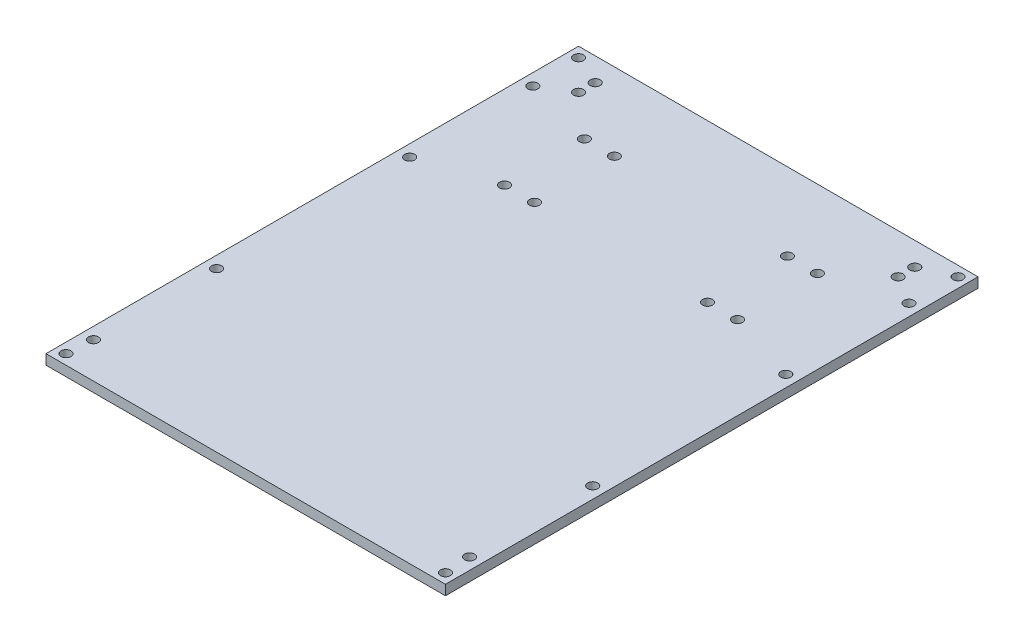
SolidWorks part; units mm, degrees
ref_plane "Front Plane" through (0, 0, 0) normal (0, 0, 1) x (1, 0, 0)
ref_plane "Top Plane" through (0, 0, 0) normal (0, 1, 0) x (1, 0, 0)
ref_plane "Right Plane" through (0, 0, 0) normal (1, 0, 0) x (0, 0, -1)
sketch "Sketch1" plane through (0, 0, 0) normal (0, 1, 0) x (1, 0, 0)
  line L1 (-120, 160) -> (0, 160)
  line L2 (-120, 160) -> (-120, 0)
  line L3 (-120, 0) -> (0, 0)
  line L4 (0, 160) -> (0, 0)
  dimension "D1" = 120
  dimension "D2" = 160
extrude "Boss-Extrude1" add sketch "Sketch1" along normal blind 3
sketch "Sketch2" plane through (0, 3, 0) normal (0, 1, 0) x (1, 0, 0)
  line L0 (-60, 160) -> (-60, 0)
  line L1 (0, 160) -> (-120, 160) construction
  line L2 (-120, 0) -> (0, 0) construction
  line L3 (0, 0) -> (0, 160) construction
  circle A0 centre (-3.5, 47.75) radius 1.5
  circle A1 centre (-3.5, 10.75) radius 1.5
  circle A2 centre (-116.5, 10.75) radius 1.5
  circle A3 centre (-116.5, 47.75) radius 1.5
  circle A4 centre (-3.5, 105.75) radius 1.5
  circle A5 centre (-3.5, 142.75) radius 1.5
  circle A6 centre (-25, 112.75) radius 1.5
  circle A7 centre (-34, 112.75) radius 1.5
  circle A8 centre (-34, 136.75) radius 1.5
  circle A9 centre (-25, 136.75) radius 1.5
  circle A10 centre (-12, 148) radius 1.5
  circle A11 centre (-12, 153) radius 1.5
  circle A12 centre (-116.5, 105.75) radius 1.5
  circle A13 centre (-95, 112.75) radius 1.5
  circle A14 centre (-86, 112.75) radius 1.5
  circle A15 centre (-86, 136.75) radius 1.5
  circle A16 centre (-95, 136.75) radius 1.5
  circle A17 centre (-116.5, 142.75) radius 1.5
  circle A18 centre (-108, 148) radius 1.5
  circle A19 centre (-108, 153) radius 1.5
  dimension "D3" = 3
  dimension "D4" = 3
  dimension "D2" = 3
  dimension "D10" = 3
  dimension "D14" = 3
  dimension "D18" = 3
  dimension "D23" = 3
  dimension "D24" = 3
  dimension "D25" = 3
  dimension "D26" = 3
  dimension "D1" = 7
  dimension "D5" = 3.5
  dimension "D6" = 3.5
  dimension "D7" = 37
  dimension "D8" = 58
  dimension "D9" = 10.75
  dimension "D11" = 12
  dimension "D12" = 5
  dimension "D13" = 12
  dimension "D15" = 3.5
  dimension "D16" = 17.25
  dimension "D17" = 37
  dimension "D19" = 24
  dimension "D20" = 9
  dimension "D21" = 9
  dimension "D22" = 24
  dimension "D27" = 23.25
  dimension "D28" = 25
  dimension "D29" = 25
  dimension "D30" = 34
extrude "Cut-Extrude12" cut sketch "Sketch2" against normal blind 3 contours A6 | A4 | A8 | A9 | A7 | A5 | A10 | A11 | A19 | A18 | A17 | A16 | A15 | A14 | A13 | A12 | A0 | A1 | A3 | A2
sketch "Sketch3" plane through (0, 3, 0) normal (0, 1, 0) x (1, 0, 0)
  line L0 (-120, 160) -> (-120, 0) construction
  line L1 (-120, 0) -> (0, 0) construction
  line L2 (0, 0) -> (0, 160) construction
  line L3 (0, 160) -> (-120, 160) construction
  circle A0 centre (-117, 157) radius 1.5
  circle A1 centre (-3, 157) radius 1.5
  circle A2 centre (-117, 3) radius 1.5
  circle A3 centre (-3, 3) radius 1.5
  dimension "D1" = 3
  dimension "D4" = 3
  dimension "D7" = 3
  dimension "D8" = 3
  dimension "D12" = 3
  dimension "D2" = 3
  dimension "D3" = 3
  dimension "D5" = 3
  dimension "D6" = 3
  dimension "D9" = 3
  dimension "D10" = 3
  dimension "D11" = 3
extrude "Cut-Extrude13" cut sketch "Sketch3" against normal blind 10
